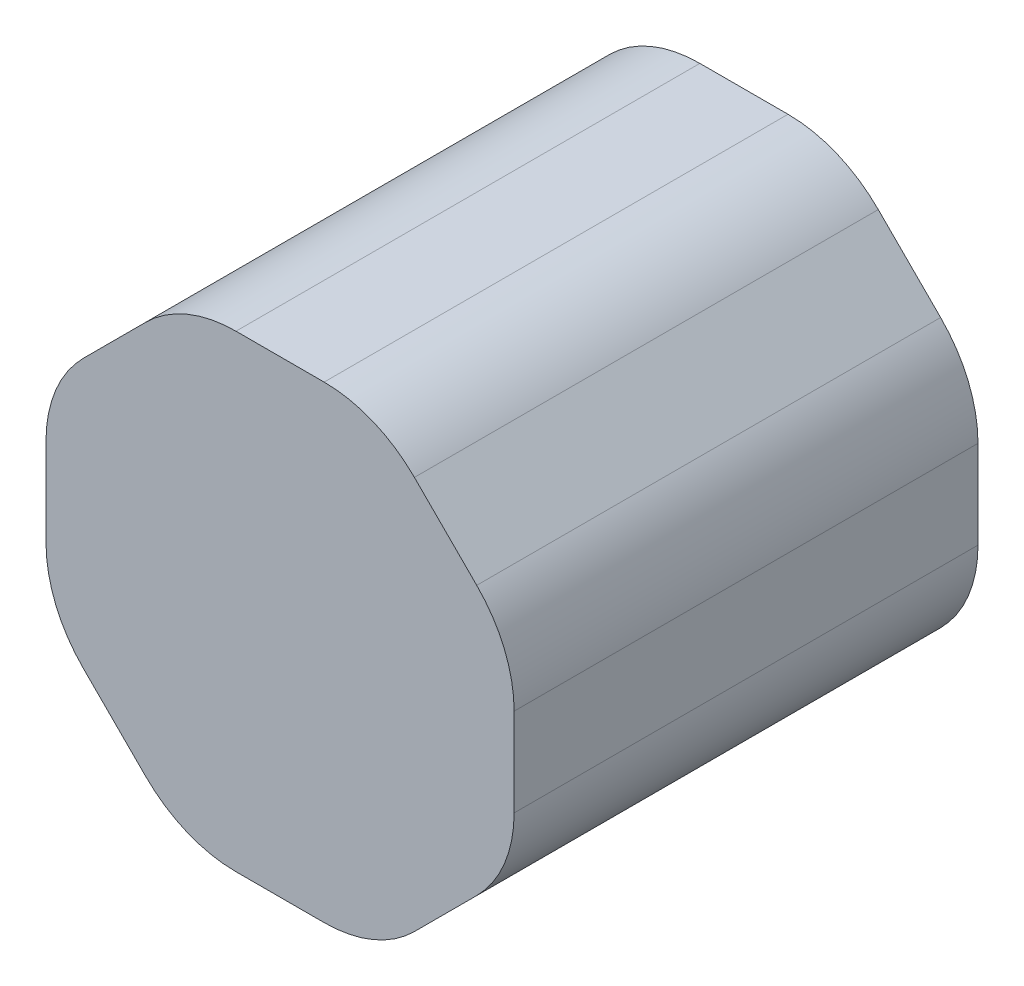
SolidWorks part; units mm, degrees
ref_plane "Plano frontal" through (0, 0, 0) normal (0, 0, 1) x (1, 0, 0)
ref_plane "Plano superior" through (0, 0, 0) normal (0, 1, 0) x (1, 0, 0)
ref_plane "Plano direito" through (0, 0, 0) normal (1, 0, 0) x (0, 0, -1)
sketch "Esboço1" plane through (0, 0, 0) normal (0, 0, 1) x (1, 0, 0)
  line L1 (55, -10.3553) -> (55, 10.3553)
  line L2 (46.2132, 31.5685) -> (31.5685, 46.2132)
  line L3 (10.3553, 55) -> (-10.3553, 55)
  line L4 (-31.5685, 46.2132) -> (-46.2132, 31.5685)
  line L5 (-55, 10.3553) -> (-55, -10.3553)
  line L6 (-46.2132, -31.5685) -> (-31.5685, -46.2132)
  line L7 (-10.3553, -55) -> (10.3553, -55)
  line L8 (31.5685, -46.2132) -> (46.2132, -31.5685)
  circle A0 centre (0, 0) radius 55 construction
  arc A1 (-55, -10.3553) -> (-46.2132, -31.5685) centre (-25, -10.3553) ccw
  arc A2 (-46.2132, 31.5685) -> (-55, 10.3553) centre (-25, 10.3553) ccw
  arc A3 (-10.3553, 55) -> (-31.5685, 46.2132) centre (-10.3553, 25) ccw
  arc A4 (31.5685, 46.2132) -> (10.3553, 55) centre (10.3553, 25) ccw
  arc A5 (55, 10.3553) -> (46.2132, 31.5685) centre (25, 10.3553) ccw
  arc A6 (55, -10.3553) -> (46.2132, -31.5685) centre (25, -10.3553) cw
  arc A7 (10.3553, -55) -> (31.5685, -46.2132) centre (10.3553, -25) ccw
  arc A8 (-31.5685, -46.2132) -> (-10.3553, -55) centre (-10.3553, -25) ccw
  dimension "D1" = 110
  dimension "D2" = 30
extrude "Ressalto-extrusão1" add sketch "Esboço1" along normal blind 109
